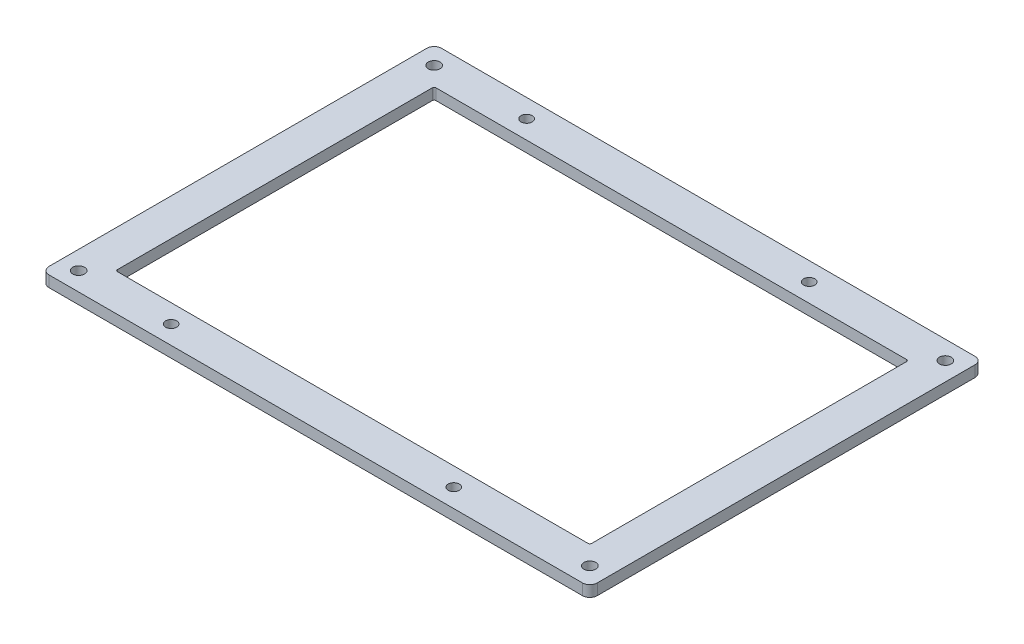
SolidWorks part; units mm, degrees
material "Acrylic (Medium-high impact)"
ref_plane "Front Plane" through (0, 0, 0) normal (0, 0, 1) x (1, 0, 0)
ref_plane "Top Plane" through (0, 0, 0) normal (0, 1, 0) x (1, 0, 0)
ref_plane "Right Plane" through (0, 0, 0) normal (1, 0, 0) x (0, 0, -1)
sketch "Sketch1" plane through (0, 0, 0) normal (0, 1, 0) x (1, 0, 0)
  line L0 (-74.1, 53.05) -> (74.1, 53.05)
  line L1 (-64.1, 43.05) -> (64.1, 43.05)
  line L2 (-64.1, 43.05) -> (-64.1, -43.05)
  line L3 (-64.1, -43.05) -> (64.1, -43.05)
  line L4 (64.1, 43.05) -> (64.1, -43.05)
  line L5 (-64.1, 43.05) -> (64.1, -43.05) construction
  line L6 (-64.1, -43.05) -> (64.1, 43.05) construction
  line L7 (74.1, 53.05) -> (74.1, -53.05)
  line L8 (-74.1, -53.05) -> (74.1, -53.05)
  line L9 (-74.1, 53.05) -> (-74.1, -53.05)
  line L10 (-74.1, 53.05) -> (-64.1, 43.05) construction
  line L11 (-74.1, 0) -> (74.1, 0) construction
  line L12 (0, 53.05) -> (0, -53.05) construction
  circle A0 centre (-69.1, 48.05) radius 1.6
  circle A1 centre (-69.1, -48.05) radius 1.6
  circle A2 centre (69.1, 48.05) radius 1.6
  circle A3 centre (69.1, -48.05) radius 1.6
  point P0 (0, 0)
  dimension "D4" = 3.2
  dimension "D1" = 86.1
  dimension "D2" = 128.2
  dimension "D3" = 10
extrude "Boss-Extrude1" add sketch "Sketch1" along normal blind 3
fillet "Fillet1" radius 2 4 edges at (74.1, 1.5, 53.05) (74.1, 1.5, -53.05) (-74.1, 1.5, -53.05) (-74.1, 1.5, 53.05)
fillet "Fillet2" radius 0.5 4 edges at (64.1, 1.5, 43.05) (64.1, 1.5, -43.05) (-64.1, 1.5, -43.05) (-64.1, 1.5, 43.05)
sketch "Sketch4" plane through (0, 3, 0) normal (0, 1, 0) x (-1, 0, 0)
  line L0 (-42.3, -38.75) -> (-42.3, -56.75) construction
  line L1 (-32.3, -43.05) -> (-32.3, -53.05) construction
  line L2 (-63.6, -43.05) -> (63.6, -43.05) construction
  line L3 (-72.1, -53.05) -> (72.1, -53.05) construction
  line L4 (74.1, -51.05) -> (74.1, 51.05) construction
  line L5 (-74.3182, 0) -> (0, 0) construction
  circle A0 centre (-32.3, -48.05) radius 1.5
  circle A1 centre (44.1, -48.05) radius 1.5
  circle A2 centre (44.1, 48.05) radius 1.5
  circle A3 centre (-32.3, 48.05) radius 1.5
  dimension "D1" = 10
  dimension "D2" = 3
  dimension "D3" = 30
extrude "Cut-Extrude3" cut sketch "Sketch4" against normal up to next
